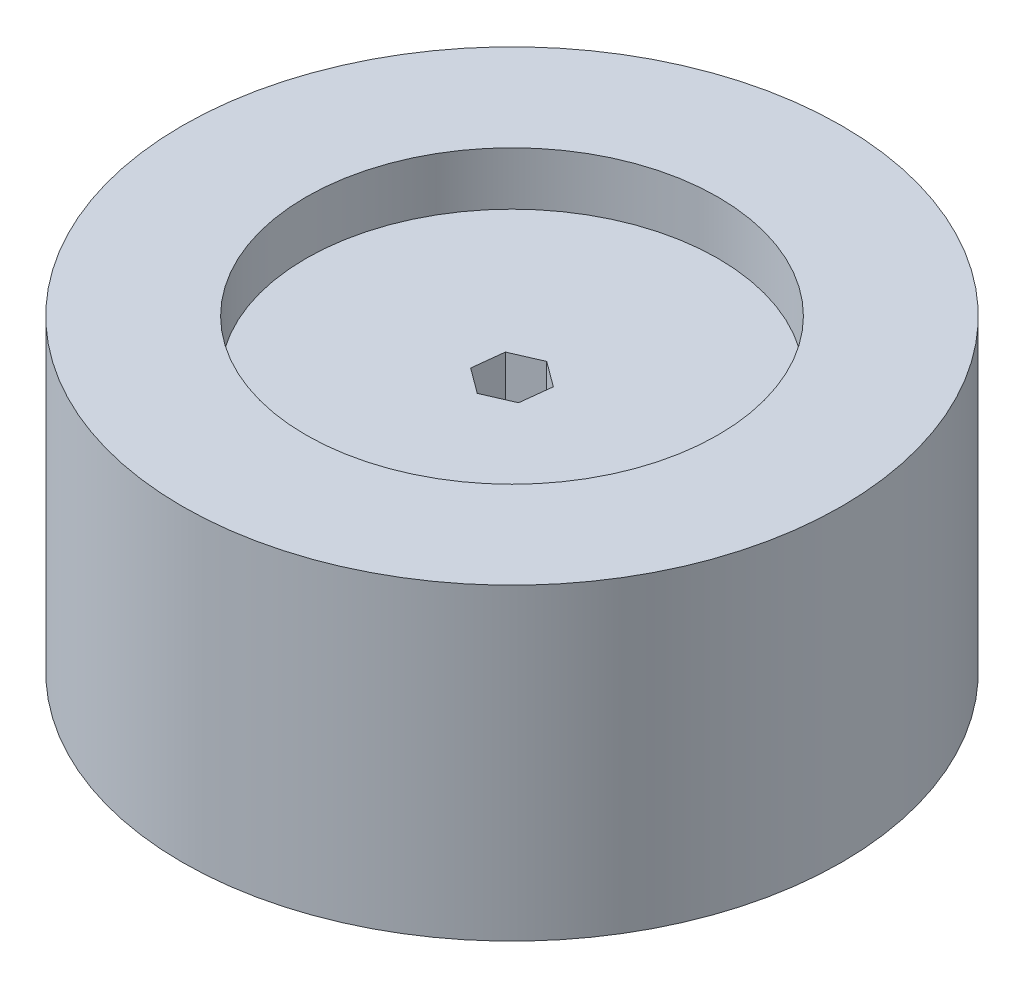
SolidWorks part; units mm, degrees
ref_plane "前视基准面" through (0, 0, 0) normal (0, 0, 1) x (1, 0, 0)
ref_plane "上视基准面" through (0, 0, 0) normal (0, 1, 0) x (1, 0, 0)
ref_plane "右视基准面" through (0, 0, 0) normal (1, 0, 0) x (0, 0, -1)
sketch "草图1" plane through (0, 0, 0) normal (0, 1, 0) x (1, 0, 0)
  circle A0 centre (0, 0) radius 40
  dimension "D1" = 80
extrude "凸台-拉伸1" add sketch "草图1" along normal blind 37.4
sketch "草图2" plane through (0, 37.4, 0) normal (0, 1, 0) x (1, 0, 0)
  line L1 (3.4934, 1.522) -> (0.4286, 3.7863)
  line L2 (0.4286, 3.7863) -> (-3.0648, 2.2643)
  line L3 (-3.0648, 2.2643) -> (-3.4934, -1.522)
  line L4 (-3.4934, -1.522) -> (-0.4286, -3.7863)
  line L5 (-0.4286, -3.7863) -> (3.0648, -2.2643)
  line L6 (3.0648, -2.2643) -> (3.4934, 1.522)
  circle A0 centre (0, 0) radius 3.3 construction
  dimension "D1" = 6.6
extrude "切除-拉伸1" cut sketch "草图2" against normal blind 16.7
sketch "草图3" plane through (0, 37.4, 0) normal (0, 1, 0) x (1, 0, 0)
  circle A0 centre (0, 0) radius 25
  dimension "D1" = 50
extrude "切除-拉伸2" cut sketch "草图3" against normal blind 6.45
sketch "草图4" plane through (0, 20.7, 0) normal (0, 1, 0) x (1, 0, 0)
  circle A0 centre (0, 0) radius 1.5
  dimension "D1" = 3
extrude "切除-拉伸3" cut sketch "草图4" against normal through all
ref_plane "基准面4" through (0, 18.7, 0) normal (0, 1, 0) x (1, 0, 0)
mirror "镜向3" about plane through (0, 18.7, 0) normal (0, 1, 0) of "切除-拉伸1", "切除-拉伸2"
